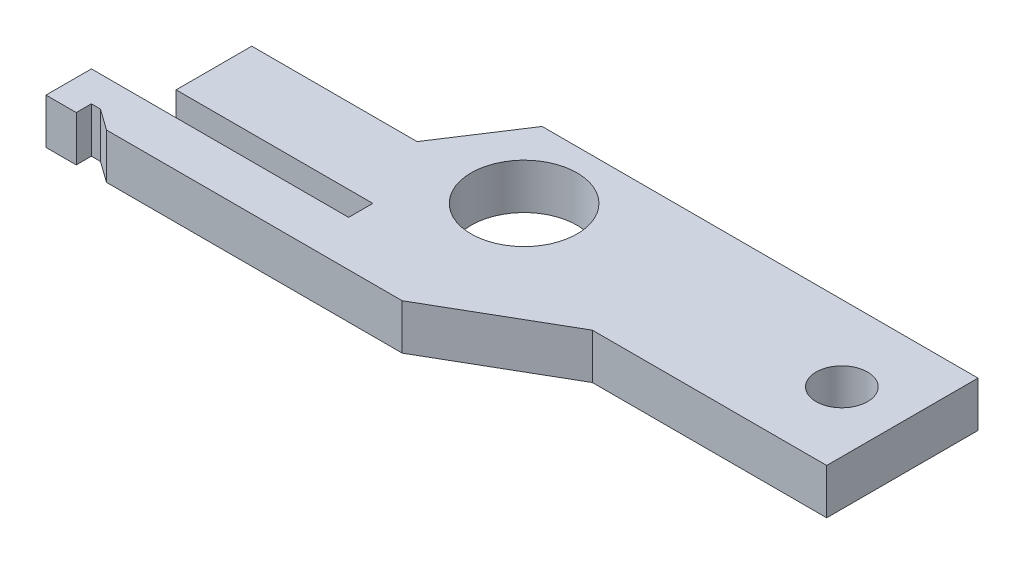
SolidWorks part; units mm, degrees
ref_plane "前视基准面" through (0, 0, 0) normal (0, 0, 1) x (1, 0, 0)
ref_plane "上视基准面" through (0, 0, 0) normal (0, 1, 0) x (1, 0, 0)
ref_plane "右视基准面" through (0, 0, 0) normal (1, 0, 0) x (0, 0, -1)
sketch "草图2" plane through (0, 7.0968, 0) normal (0, 1, 0) x (1, 0, 0)
  line L0 (-1.9, 0) -> (-10.4, 0)
  line L1 (-6.9, 0.7) -> (-6.9, 0) construction
  line L2 (-1.9, 0) -> (-1.9, 0.8)
  line L3 (-1.9, 0.8) -> (-8.4, 0.8)
  line L4 (-6.9, 0.7) -> (-1.9, 0.7) construction
  line L5 (-10.4, 0) -> (-10.4, -1.5)
  line L6 (-10.4, -1.5) -> (-9.4, -1.5)
  line L7 (13.1, 0.8) -> (13.1, 5.8)
  line L8 (-9.4, -1) -> (-9.1, -1)
  line L9 (-9.1, -1) -> (-8.4, -1.5)
  line L10 (-1.3034, 5.8) -> (-2.9368, 3.3)
  line L11 (13.1, 5.8) -> (-1.3034, 5.8)
  line L12 (-8.4, 3.3) -> (-8.4, 0.8)
  line L13 (-9.4, -1.5) -> (-9.4, -1)
  line L15 (1.3718, -1.5) -> (5.3555, 0.8)
  line L16 (5.3555, 0.8) -> (13.1, 0.8)
  line L17 (-8.4, -1.5) -> (1.3718, -1.5)
  line L18 (-2.9368, 3.3) -> (-8.4, 3.3)
  circle A0 centre (11.1, 3.3) radius 0.85
  circle A1 centre (0.6, 3.3) radius 1.75
  dimension "D4" = 1.7
  dimension "D5" = 3.5
  dimension "D1" = 0.1
  dimension "D2" = 1.5
  dimension "D6" = 10.5
  dimension "D7" = 1
  dimension "D8" = 2.5
  dimension "D9" = 0.5
  dimension "D10" = 10
  dimension "D11" = 1.5
  dimension "D12" = 1
  dimension "D13" = 2
  dimension "D14" = 30
  dimension "D15" = 2.5
  dimension "D3" = 5
  dimension "D16" = 0.3
extrude "凸台-拉伸1" add sketch "草图2" against normal blind 1.5
equation "\"D8@草图2\"=\"D3@草图2\"/2"
